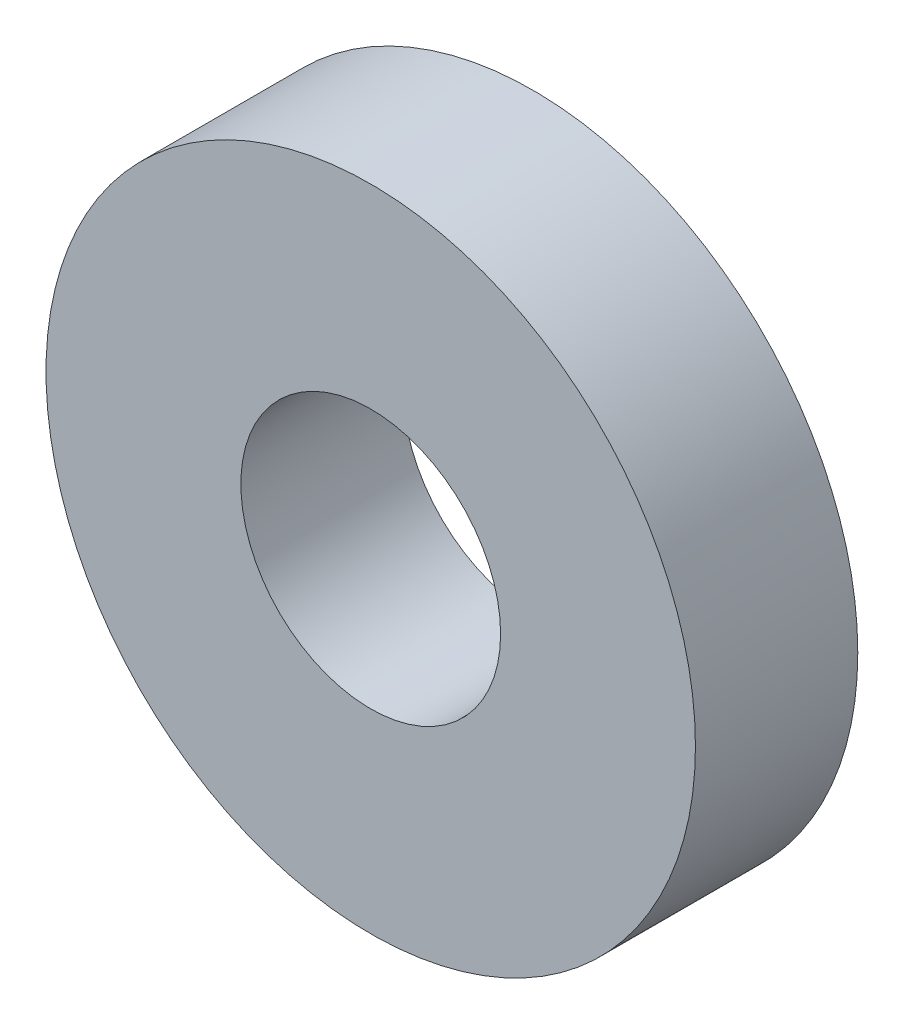
SolidWorks part; units mm, degrees
ref_plane "Front Plane" through (0, 0, 0) normal (0, 0, 1) x (1, 0, 0)
ref_plane "Top Plane" through (0, 0, 0) normal (0, 1, 0) x (1, 0, 0)
ref_plane "Right Plane" through (0, 0, 0) normal (1, 0, 0) x (0, 0, -1)
sketch "Sketch1" plane through (0, 0, 0) normal (0, 0, 1) x (1, 0, 0)
  line L0 (0, 1.6) -> (0, 4) construction
  line L1 (0, -1.6) -> (0, -4) construction
  circle A0 centre (0, 0) radius 4
  circle A1 centre (0, 0) radius 1.6
  dimension "OD" = 8
  dimension "ID" = 3.2
sketch "Sketch2" plane through (0, 0, 0) normal (1, 0, 0) x (0, 0, -1)
  line L0 (-1, 1.6) -> (1, 1.6) construction
  line L1 (-1, -1.6) -> (1, -1.6) construction
  line L2 (-1, -4) -> (1, -4) construction
  line L3 (-1, 4) -> (1, 4) construction
  dimension "Length" = 2
extrude "Extrude1" add sketch "Sketch1" along normal up to vertex (1 mm away) and the other way up to vertex (1 mm away) up to point (0, 1.6, 1) other way up to point (0, 1.6, -1)
sketch "Sketch3" plane through (0, 0, 1) normal (0, 0, 1) x (1, 0, 0)
  circle A0 centre (0, 0) radius 1.6 construction
  circle A3 centre (0, 0) radius 1.6
  point P3 (-1.6, 0)
